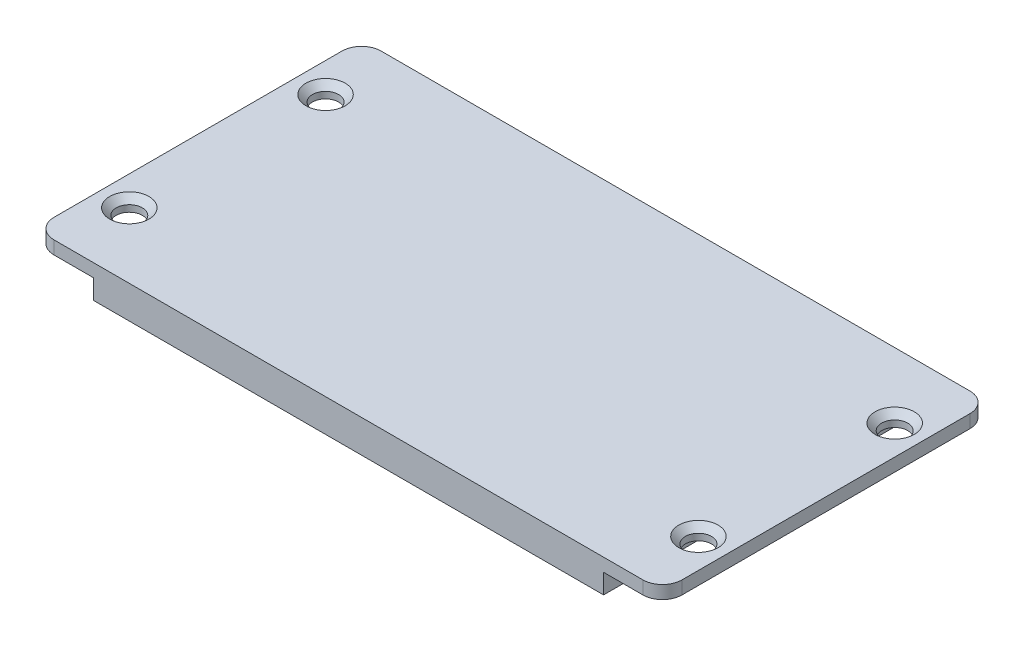
SolidWorks part; units mm, degrees
ref_plane "Plan de face" through (0, 0, 0) normal (0, 0, 1) x (1, 0, 0)
ref_plane "Plan de dessus" through (0, 0, 0) normal (0, 1, 0) x (1, 0, 0)
ref_plane "Plan de droite" through (0, 0, 0) normal (1, 0, 0) x (0, 0, -1)
sketch "Esquisse1" plane through (0, 0, 0) normal (0, 1, 0) x (1, 0, 0)
  line L1 (-45, 25) -> (45, 25)
  line L2 (-48, 22) -> (-48, -22)
  line L3 (-45, -25) -> (45, -25)
  line L4 (48, 22) -> (48, -22)
  arc A0 (-48, -22) -> (-45, -25) centre (-45, -22) ccw
  arc A1 (45, -25) -> (48, -22) centre (45, -22) ccw
  arc A2 (45, 25) -> (48, 22) centre (45, 22) cw
  arc A3 (-45, 25) -> (-48, 22) centre (-45, 22) ccw
  circle A4 centre (-43.5, 15) radius 2
  circle A5 centre (43.5, 15) radius 2
  circle A6 centre (43.5, -15) radius 2
  circle A7 centre (-43.5, -15) radius 2
  dimension "D1" = 3
  dimension "D8" = 4
  dimension "D2" = 25
  dimension "D3" = 50
  dimension "D4" = 96
  dimension "D5" = 48
  dimension "D6" = 10
  dimension "D7" = 4.5
  dimension "D9" = 10
  dimension "D10" = 4.5
extrude "Boss.-Extru.1" add sketch "Esquisse1" against normal blind 5
chamfer "Chanfrein1" distance 1 angle 45 4 edges at (43.5, 0, -13) (43.5, 0, 17) (-43.5, 0, 17) (-43.5, 0, -13)
sketch "Esquisse2" plane through (0, -5, 0) normal (0, -1, 0) x (-1, 0, 0)
  line L0 (45, -25) -> (-45, -25) construction
  line L1 (39, -25) -> (48, -25)
  line L2 (39, -25) -> (39, 25)
  line L3 (39, 25) -> (48, 25)
  line L4 (48, -25) -> (48, 25)
  line L5 (-39, -25) -> (-48, -25)
  line L6 (-39, -25) -> (-39, 25)
  line L7 (-39, 25) -> (-48, 25)
  line L8 (-48, -25) -> (-48, 25)
  line L9 (-45, 25) -> (45, 25) construction
  line L10 (48, 22) -> (48, -22) construction
  line L11 (-48, -22) -> (-48, 22) construction
  dimension "D1" = 9
extrude "Enlèv. mat.-Extru.1" cut sketch "Esquisse2" against normal blind 3
